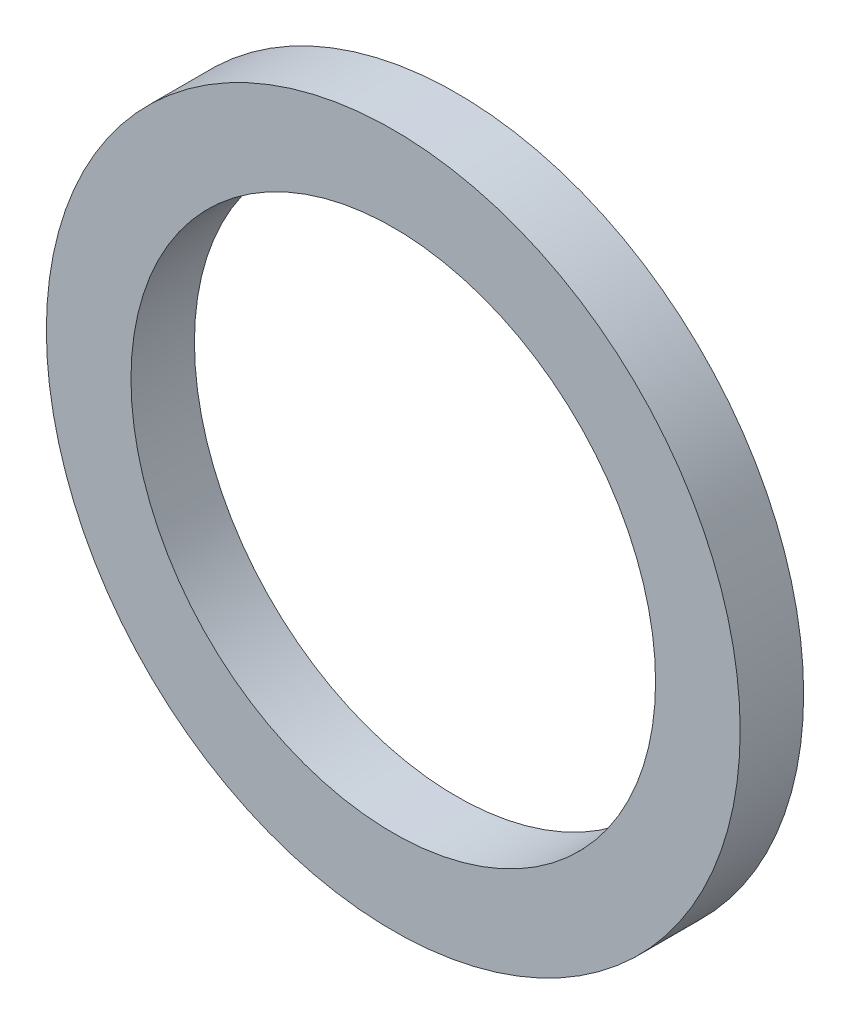
SolidWorks part; units mm, degrees
ref_plane "XZ (Face)" through (0, 0, 0) normal (0, 0, 1) x (1, 0, 0)
ref_plane "XY (Dessus)" through (0, 0, 0) normal (0, 1, 0) x (1, 0, 0)
ref_plane "YZ (Droite)" through (0, 0, 0) normal (1, 0, 0) x (0, 0, -1)
sketch "Esquisse1" plane through (0, 0, 0) normal (0, 0, 1) x (1, 0, 0)
  circle A2 centre (0, 0) radius 4.1
  circle A3 centre (0, 0) radius 3.1
  circle A4 centre (0, 0) radius 3.1
  dimension "D1" = 0.7
  dimension "D2" = 1
extrude "Base-Extrusion" add sketch "Esquisse1" along normal blind 0.75
